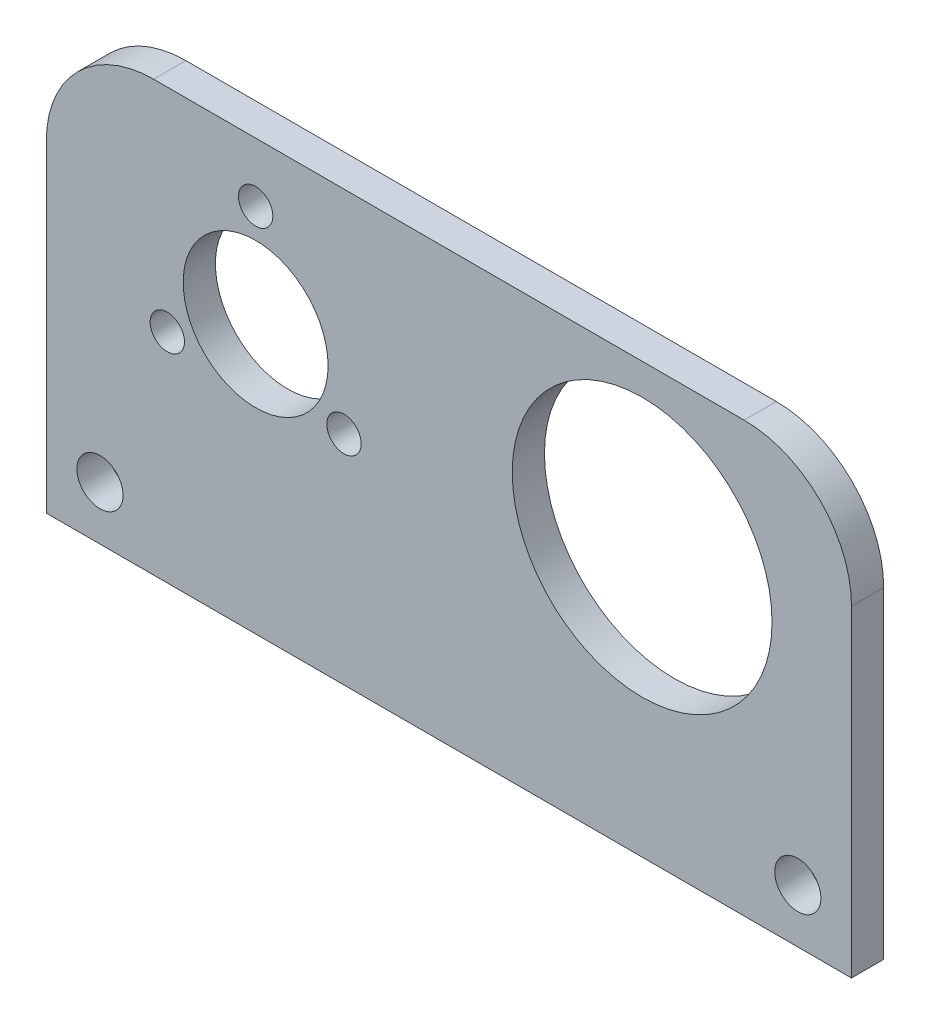
SolidWorks part; units mm, degrees
material "5052-H34"
ref_plane "正面" through (0, 0, 0) normal (0, 0, 1) x (1, 0, 0)
ref_plane "平面" through (0, 0, 0) normal (0, 1, 0) x (1, 0, 0)
ref_plane "右側面" through (0, 0, 0) normal (1, 0, 0) x (0, 0, -1)
sketch "ｽｹｯﾁ1" plane through (0, 0, 0) normal (0, 0, 1) x (1, 0, 0)
  line L0 (19.5, 25) -> (19.5, 34.5) construction
  line L1 (0, 0) -> (75, 0)
  line L2 (0, 0) -> (0, 40)
  line L3 (0, 40) -> (75, 40)
  line L4 (75, 0) -> (75, 40)
  line L5 (19.5, 25) -> (55.5, 25) construction
  line L6 (37.5, 40) -> (37.5, 0) construction
  circle A0 centre (19.5, 25) radius 6.75
  circle A1 centre (19.5, 34.5) radius 1.6
  circle A2 centre (27.7272, 20.25) radius 1.6
  circle A3 centre (11.2728, 20.25) radius 1.6
  circle A5 centre (55.5, 25) radius 12.1
  circle A6 centre (5, 5) radius 2.15
  circle A7 centre (70, 5) radius 2.15
  point P15 (19.5, 25)
  point P17 (37.5, 25)
  dimension "D1" = 13.5
  dimension "D3" = 3.2
  dimension "D4" = 24.2
  dimension "D9" = 4.3
  dimension "D2" = 9.5
  dimension "D5" = 40
  dimension "D6" = 75
  dimension "D7" = 25
  dimension "D8" = 36
  dimension "D10" = 5
  dimension "D11" = 5
extrude "ﾎﾞｽ - 押し出し1" add sketch "ｽｹｯﾁ1" along normal blind 3
fillet "ﾌｨﾚｯﾄ1" radius 10 2 edges at (75, 40, 1.5) (0, 40, 1.5)
